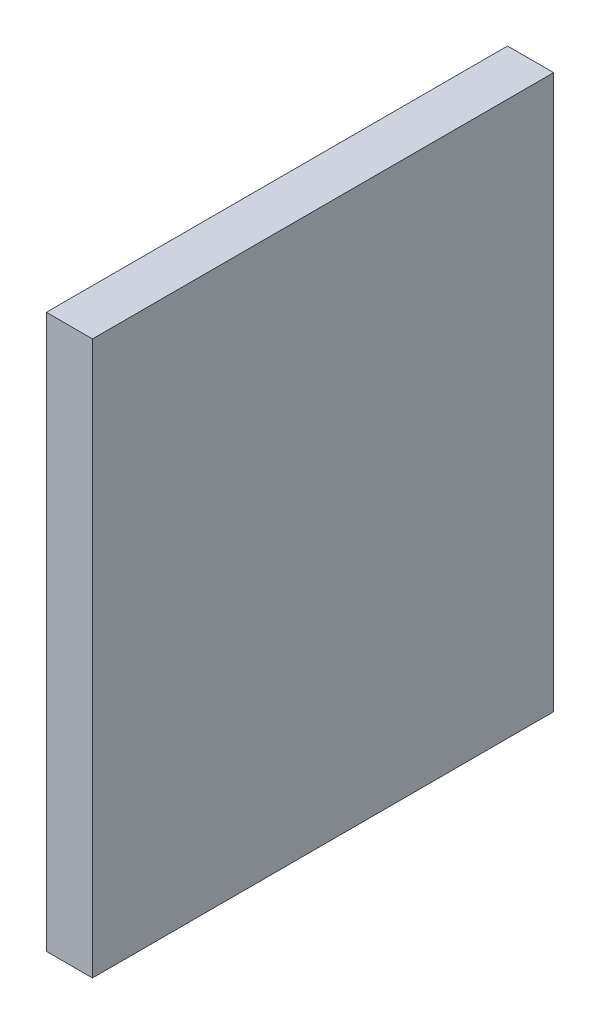
SolidWorks part; units mm, degrees
ref_plane "Спереди" through (0, 0, 0) normal (0, 0, 1) x (1, 0, 0)
ref_plane "Сверху" through (0, 0, 0) normal (0, 1, 0) x (1, 0, 0)
ref_plane "Справа" through (0, 0, 0) normal (1, 0, 0) x (0, 0, -1)
sketch "Эскиз1" plane through (0, 0, 0) normal (1, 0, 0) x (0, 0, -1)
  line L0 (30.0023, 36.9294) -> (30.0023, 44.4284) construction
  line L1 (0, -2) -> (60, -2)
  line L2 (0, -2) -> (0, -74)
  line L3 (0, -74) -> (60, -74)
  line L4 (60, -2) -> (60, -74)
  line L5 (0, -2) -> (60, -2) construction
extrude "Вытянуть1" add sketch "Эскиз1" along normal blind 6
